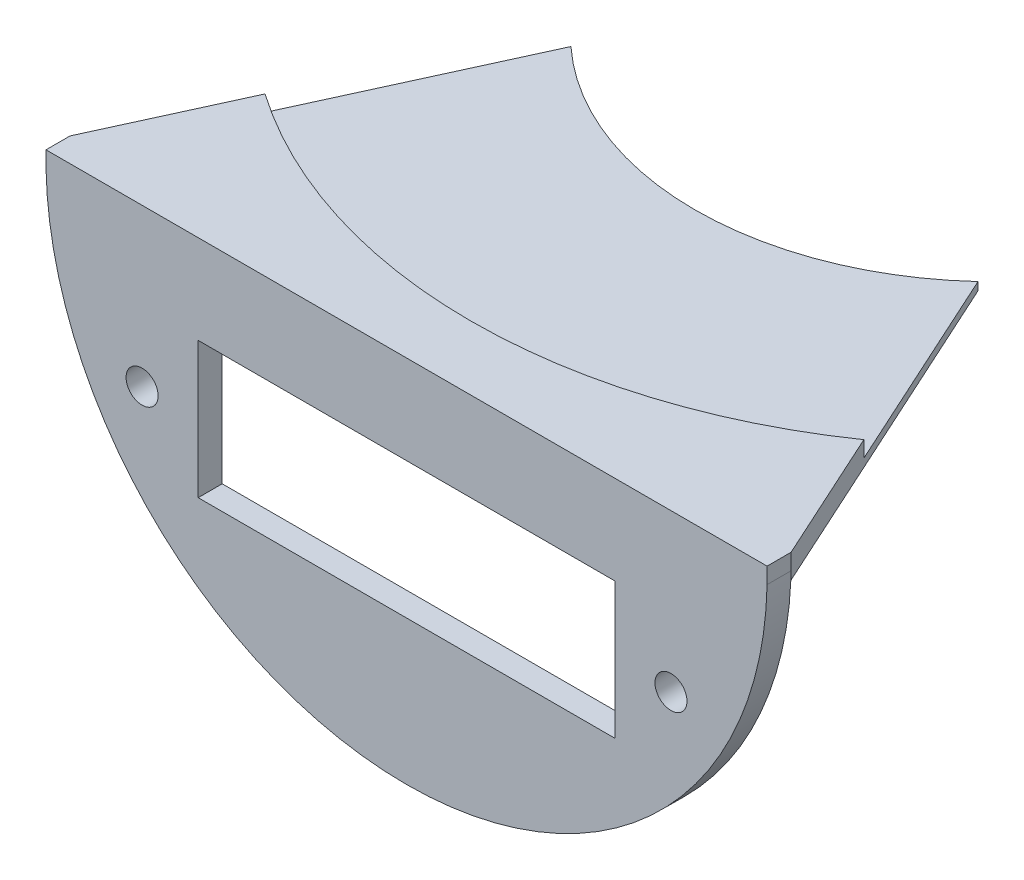
SolidWorks part; units mm, degrees
ref_plane "Front Plane" through (0, 0, 0) normal (0, 0, 1) x (1, 0, 0)
ref_plane "Top Plane" through (0, 0, 0) normal (0, 1, 0) x (1, 0, 0)
ref_plane "Right Plane" through (0, 0, 0) normal (1, 0, 0) x (0, 0, -1)
sketch "Sketch1" plane through (0, 0, 0) normal (0, 0, 1) x (1, 0, 0)
  line L0 (-44.991, 29.1) -> (44.991, 29.1)
  line L3 (-26, 3) -> (26, 3)
  line L4 (-26, 3) -> (-26, 20)
  line L5 (-26, 20) -> (26, 20)
  line L6 (26, 3) -> (26, 20)
  arc A0 (-44.991, 29.1) -> (44.991, 29.1) centre (0, 30) ccw
  circle A2 centre (-33, 11.5) radius 2
  circle A3 centre (33, 11.5) radius 2
  point P18 (26, 11.5)
  point P19 (-26, 11.5)
  dimension "D1" = 90
  dimension "D2" = 4
  dimension "D3" = 4
extrude "Boss-Extrude1" add sketch "Sketch1" along normal blind 3
sketch "Sketch4" plane through (0, 28.1, 0) normal (0, 1, 0) x (1, 0, 0)
  line L0 (-25.4, 42.9121) -> (-44.991, 0)
  line L1 (44.991, 0) -> (-44.991, 0) construction
  line L2 (-25.4, 25.5) -> (-25.4, 85) construction
  line L3 (25.4, 42.9121) -> (44.991, 0)
  line L4 (25.4, 85) -> (25.4, 25.5) construction
  line L6 (44.991, 0) -> (-44.991, 0)
  circle A0 centre (0, 70.5) radius 37.5 construction
  arc A1 (25.4, 42.9121) -> (-25.4, 42.9121) centre (0, 70.5) cw
  circle A2 centre (0, 70.5) radius 6.7945 construction
extrude "Boss-Extrude2" add sketch "Sketch4" along normal up to surface (1 mm away)
sketch "Sketch5" plane through (0, 29.1, 0) normal (0, 1, 0) x (1, 0, 0)
  line L0 (-44.991, 0) -> (-25.4, 42.9121) construction
  line L1 (25.4, 42.9121) -> (44.991, 0) construction
  line L2 (-37.3653, 16.7033) -> (-44.991, 0)
  line L3 (-44.991, 0) -> (-44.991, -3)
  line L4 (-44.991, -3) -> (44.991, -3)
  line L5 (44.991, -3) -> (44.991, 0)
  line L6 (44.991, 0) -> (37.3653, 16.7033)
  arc A0 (-37.3653, 16.7033) -> (37.3653, 16.7033) centre (0, 70.5) ccw
  dimension "D1" = 65.5
extrude "Boss-Extrude3" add sketch "Sketch5" along normal blind 2
